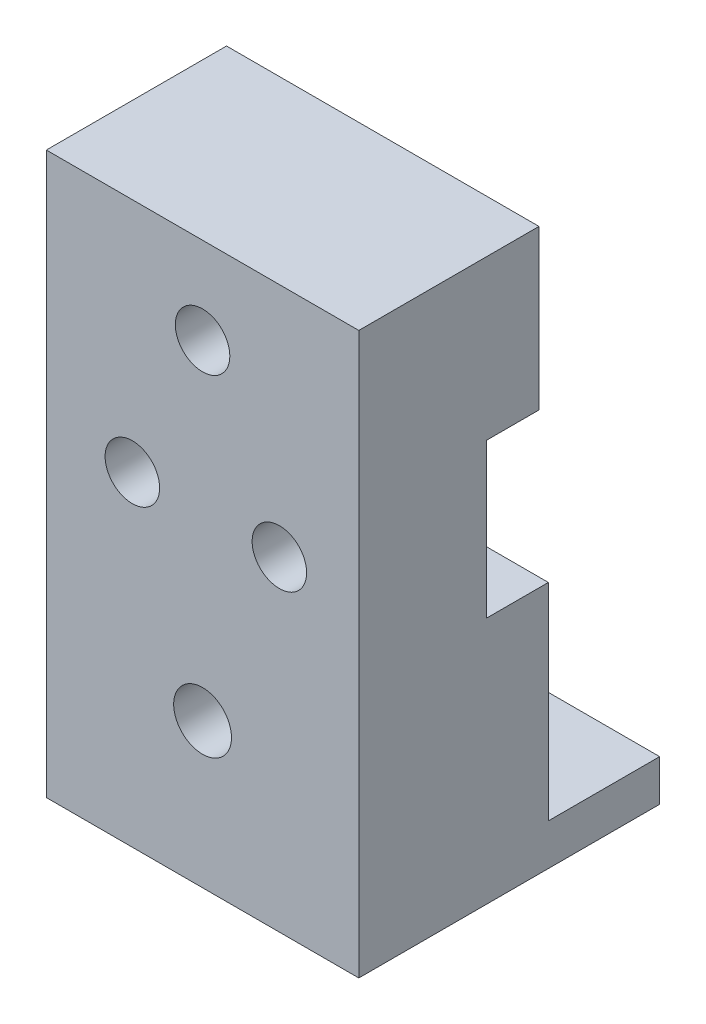
SolidWorks part; units mm, degrees
other "Markup1"
sketch "Sketch38" plane through (29.55, 20.3673, 21.6582) normal (0.6559, 0.2777, 0.7019) x (0.7528, -0.1717, -0.6355)
ref_plane "Front Plane" through (0, 0, 0) normal (0, 0, 1) x (1, 0, 0)
ref_plane "Top Plane" through (0, 0, 0) normal (0, 1, 0) x (1, 0, 0)
ref_plane "Right Plane" through (0, 0, 0) normal (1, 0, 0) x (0, 0, -1)
ref_plane "Plane3" through (0, -152.4, 0) normal (0, 1, 0) x (1, 0, 0)
ref_plane "Plane4" through (0, -200, 0) normal (0, 1, 0) x (1, 0, 0)
ref_plane "Plane5" through (0, -62.9, 0) normal (0, -1, 0) x (-1, 0, 0)
sketch "Sketch40" plane through (0, -62.9, 0) normal (0, -1, 0) x (-1, 0, 0)
  line L0 (20, 0) -> (-20, 0) construction
  ellipse E1 centre (0, 0) end of major axis (-20, 0) minor radius 17.5
  point P3 (0, 0)
  dimension "D1" = 35
  dimension "D2" = 40
sketch "Sketch1" plane through (0, 0, 0) normal (0, 1, 0) x (1, 0, 0)
  circle A0 centre (0, 0) radius 22.5
  point P5 (-22.5, 0)
  dimension "D1" = 45
sketch "Sketch2" plane through (0, -200, 0) normal (0, 1, 0) x (1, 0, 0)
  circle A0 centre (0, 0) radius 19.05
  point P5 (-19.05, 0)
  dimension "D1" = 38.1
sketch "Sketch3" plane through (0, -152.4, 0) normal (0, 1, 0) x (1, 0, 0)
  line L0 (-19.6977, 0) -> (19.6977, 0) construction
  ellipse E0 centre (0, 0) end of major axis (19.6977, 0) minor radius 12.5
  point P12 (-19.6977, 0)
  dimension "D1" = 25
  dimension "D2" = 39.3954
sketch "Sketch8" plane through (0, 0, 0) normal (0, 0, 1) x (1, 0, 0)
  line L0 (-20, -62.9) -> (20, -62.9) construction
  line L1 (-20, -62.9) -> (20, -62.9) construction
  line L2 (19.05, -200) -> (-19.05, -200) construction
  line L3 (22.5, 0) -> (-22.5, 0) construction
  line L4 (-19.6977, -152.4) -> (19.6977, -152.4) construction
  line L5 (19.05, -200) -> (-19.05, -200) construction
  line L6 (22.5, 0) -> (-22.5, 0) construction
  line L7 (-19.6977, -152.4) -> (19.6977, -152.4) construction
  line L8 (0, -200) -> (0, 0) construction
  spline S0 degree 3 poles (-22.5, 0) (-17.85, -66.5922) (-20.875, -133.3359) (-19.05, -200) knots 0 0 0 0 1 1 1 1
sketch "Sketch31" plane through (0, 0, 0) normal (0, 0, 1) x (1, 0, 0)
  line L3 (-18.6511, 2) -> (19.4489, 2)
  line L4 (-18.6511, 2) -> (-18.6511, 0)
  line L5 (19.4489, 0) -> (19.4489, 2)
  line L6 (0, -10.5) -> (0.3989, -50.4) construction
  line L7 (9.2989, -28.575) -> (-8.5011, -28.575) construction
  line L8 (-18.6511, 0) -> (19.4489, 0) construction
  circle A5 centre (0.3989, -50.4) radius 3.25
  circle A6 centre (9.2989, -28.575) radius 3.25
  circle A7 centre (-8.5011, -28.575) radius 3.25
  circle A8 centre (-15.4572, 18.8673) radius 1.5
  circle A9 centre (0, -10.5) radius 3.25
  dimension "D5" = 3
  dimension "D6" = 6.5
  dimension "D9" = 6.5
  dimension "D10" = 6.5
  dimension "D11" = 6.5
  dimension "D1" = 15.4572
  dimension "D2" = 18.8673
  dimension "D3" = 2
  dimension "D4" = 18.6511
  dimension "D7" = 38.1
  dimension "D8" = 17.8
  dimension "D12" = 28.575
  dimension "D13" = 39.9
  dimension "D14" = 10.5
  dimension "D15" = 8.5011
  dimension "D16" = 89.427
  dimension "D17" = 15.4572
sketch "Sketch32" plane through (0, 0, 0) normal (1, 0, 0) x (0, 0, -1)
  line L0 (-26.8006, 0) -> (-26.8006, -62.9)
  line L1 (11.7549, -62.9) -> (11.2977, -62.9) construction
  line L2 (-26.8006, 0) -> (-19.3486, 0)
  line L3 (-26.8006, -62.9) -> (4.5252, -62.9) construction
  line L7 (-19.3486, 0) -> (2.8894, 0)
  line L8 (4.5252, -62.9) -> (11.2977, -62.9)
  line L9 (4.0252, -38.4) -> (4.0252, -62.4)
  line L10 (-2.9606, -37.9) -> (3.5252, -37.9)
  line L11 (-3.4606, -19.75) -> (-3.4606, -37.4)
  line L12 (2.3894, -19.25) -> (-2.9606, -19.25)
  line L13 (2.8894, 0) -> (2.8894, -18.75)
  arc A5 (4.0252, -62.4) -> (4.5252, -62.9) centre (4.5252, -62.4) ccw
  arc A6 (4.0252, -38.4) -> (3.5252, -37.9) centre (3.5252, -38.4) ccw
  arc A7 (-3.4606, -37.4) -> (-2.9606, -37.9) centre (-2.9606, -37.4) ccw
  arc A8 (-2.9606, -19.25) -> (-3.4606, -19.75) centre (-2.9606, -19.75) ccw
  arc A9 (2.3894, -19.25) -> (2.8894, -18.75) centre (2.3894, -18.75) ccw
  dimension "D8" = 0.5
  dimension "D9" = 0.5
  dimension "D10" = 0.5
  dimension "D11" = 0.5
  dimension "D12" = 0.5
  dimension "D1" = 2.8894
  dimension "D2" = 3.4606
  dimension "D3" = 19.25
  dimension "D4" = 18.65
  dimension "D5" = 25
  dimension "D6" = 4.0252
  dimension "D7" = 19.3486
  dimension "D13" = 7.2726
  dimension "D14" = 0.4572
  dimension "D15" = 29.69
sketch "Sketch41" plane through (0, 0, 0) normal (1, 0, 0) x (0, 0, -1)
  line L0 (4.5252, -62.9) -> (11.2977, -62.9) construction
  line L1 (4.0252, -38.4) -> (4.0252, -62.4) construction
  line L2 (-2.9606, -37.9) -> (3.5252, -37.9) construction
  line L3 (-3.4606, -19.75) -> (-3.4606, -37.4) construction
  line L4 (2.3894, -19.25) -> (-2.9606, -19.25) construction
  line L5 (2.8894, 0) -> (2.8894, -18.75) construction
  line L7 (4.0252, -62.9) -> (17.5, -62.9)
  line L8 (4.0252, -37.9) -> (4.0252, -62.9)
  line L9 (-3.4606, -37.9) -> (4.0252, -37.9)
  line L10 (-3.4606, -19.25) -> (-3.4606, -37.9)
  line L11 (2.8894, -19.25) -> (-3.4606, -19.25)
  line L12 (2.8894, 0) -> (2.8894, -19.25)
  line L13 (-18.925, 0) -> (-18.925, -67.9)
  line L14 (-18.925, 0) -> (2.8894, 0)
  line L15 (2.8894, 0) -> (4.0252, 0) construction
  line L16 (-3.4606, 0) -> (-3.4606, -19.25) construction
  line L17 (4.0252, 0) -> (4.0252, -37.9) construction
  line L18 (-26.8006, -62.9) -> (0, -62.9) construction
  line L19 (-18.925, -37.9) -> (-3.4606, -37.9) construction
  line L20 (2.8894, -19.25) -> (2.8894, -37.9) construction
  line L22 (17.5, -67.9) -> (-18.925, -67.9)
  line L23 (-12.405, -67.9) -> (-12.405, -85.56) construction
  line L24 (0, -85.56) -> (17.5, -85.56) construction
  line L25 (17.5, -85.56) -> (17.5, -105.56) construction
  line L26 (17.5, -105.56) -> (0, -105.56) construction
  line L27 (0, 0) -> (0, -105.56) construction
  line L28 (17.5, -67.9) -> (17.5, -62.9)
  line L29 (-17.5, -62.9) -> (17.5, -62.9) construction
  line L30 (-17.5, -62.9) -> (0, -62.9) construction
  line L31 (0, -62.9) -> (4.0252, -62.9) construction
  line L32 (4.0252, -62.9) -> (17.5, -62.9) construction
  line L33 (0, -62.9) -> (4.0252, -62.9) construction
  line L34 (0, -62.9) -> (4.0252, -62.9) construction
  line L35 (17.5, -67.9) -> (17.5, -85.56) construction
  line L36 (-18.925, -67.9) -> (-18.925, -105.56) construction
  line L37 (-12.405, -85.56) -> (0, -85.56) construction
  line L38 (0, -105.56) -> (-18.925, -105.56) construction
  point P10 (-0.7125, -100.905)
  point P37 (0, 0)
  point P39 (0, 0)
  point P40 (0, 0)
  dimension "D1" = 17.66
  dimension "D2" = 20
  dimension "D3" = 5
  dimension "D5" = 105.56
  dimension "D4" = 18.925
  dimension "D6" = 12.405
  dimension "D7" = 67.9
  dimension "D8" = 19.25
  dimension "D9" = 18.65
  dimension "D10" = 62.9
  dimension "D11" = 21.8144
  dimension "D12" = 15.4644
  dimension "D13" = 22.9502
  dimension "D14" = 36.425
extrude "Boss-Extrude1" add sketch "Sketch41" along normal mid plane 37.83
sketch "Sketch42" plane through (0, 0, 0) normal (0, 0, 1) x (1, 0, 0)
  line L0 (0, 0) -> (0, -73.5231) construction
  line L2 (18.915, 0) -> (-18.915, 0) construction
  line L3 (0.3989, -50.4) -> (0, -50.4) construction
  line L4 (9.2989, -28.575) -> (-8.5011, -28.575) construction
  line L5 (9.2989, -28.575) -> (-8.5011, -28.575) construction
  circle A0 centre (0, -10.5) radius 3.25 construction
  circle A1 centre (0.3989, -50.4) radius 3.25 construction
  circle A2 centre (0, -10.5) radius 3.25 construction
  circle A3 centre (0.3989, -50.4) radius 3.25 construction
  circle A4 centre (0, -10.5) radius 3.3
  circle A5 centre (0, -50.4) radius 3.5
  circle A6 centre (9.2989, -28.575) radius 3.25 construction
  circle A7 centre (-8.5011, -28.575) radius 3.25 construction
  circle A8 centre (9.2989, -28.575) radius 3.25 construction
  circle A9 centre (-8.5011, -28.575) radius 3.25 construction
  circle A10 centre (-8.5011, -28.575) radius 3.3
  circle A11 centre (9.2989, -28.575) radius 3.3
  point P3 (0, -73.5231)
  dimension "D1" = 6.6
  dimension "D2" = 7
  dimension "D3" = 6.6
  dimension "D4" = 6.6
  dimension "D5" = 73.5231
  dimension "D6" = 17.8
  dimension "D7" = 39.9
  dimension "D8" = 10.5
extrude "Cut-Extrude1" cut sketch "Sketch42" against normal through all both and the other way through all
equation "\"BoltHeadDiameter\"= 10.5"
equation "\"CableDiameter\"= 8"
equation "\"CableRingRadius\"= 8"
equation "\"D9@Sketch31\"=\"D6@Sketch31\""
equation "\"D10@Sketch31\"=\"D6@Sketch31\""
equation "\"D11@Sketch31\"=\"D6@Sketch31\""
equation "\"8020_width\"= 37.85"
equation "\"BoltLengthMax\"= 60"
equation "\"BoltLengthMin\"= 55"
equation "\"washerStackheight\"= 3.7'uncompressed"
equation "\"NutHeight-5/16\"= 6.92"
equation "\"NutWidthMin-5/16\"= 12.83"
equation "\"NutWidthMax-5/6\"= 14.51"
equation "\"WrenchClearance\"= 28'half-inch wrench for five sixteenths"
equation "\"WrenchHeightClearance\"= 16.66'Closed wrench plus nut height"
equation "\"D1@Sketch41\"=\"WrenchHeightClearance\"+1"
equation "\"ClosedWrenchDiameter\"= 20.81"
equation "\"D1@Boss-Extrude1\"=\"8020_width\"-.02"
equation "\"ClearanceHole-M6\"= 6.6'normal"
equation "\"ClearanceHole-5/16\"= 8.74"
equation "\"D1@Sketch42\"=\"ClearanceHole-M6\""
equation "\"D2@Sketch42\"=\"ClearanceHole-M6\"+.4"
equation "\"D3@Sketch42\"=\"ClearanceHole-M6\""
equation "\"D4@Sketch42\"=\"ClearanceHole-M6\""
equation "\"D4@Sketch41\"=\"8020_width\"/2"
equation "\"D6@Sketch41\"=\"ClosedWrenchDiameter\"/2+2"
